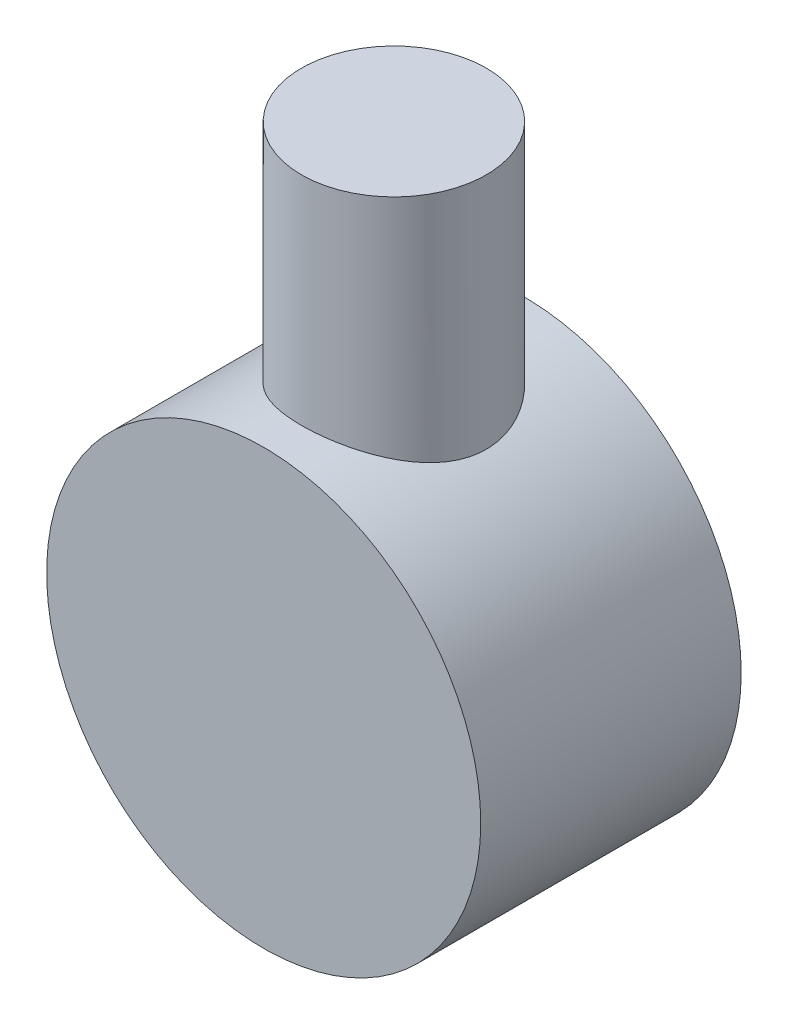
SolidWorks part; units mm, degrees
ref_plane "Front Plane" through (0, 0, 0) normal (0, 0, 1) x (1, 0, 0)
ref_plane "Top Plane" through (0, 0, 0) normal (0, 1, 0) x (1, 0, 0)
ref_plane "Right Plane" through (0, 0, 0) normal (1, 0, 0) x (0, 0, -1)
sketch "Sketch1" plane through (0, 0, 0) normal (0, 0, 1) x (1, 0, 0)
  circle A0 centre (0, 0) radius 25
  dimension "D1" = 50
extrude "Boss-Extrude1" add sketch "Sketch1" along normal mid plane 30
sketch "Sketch2" plane through (0, 0, 0) normal (0, 1, 0) x (1, 0, 0)
  circle A0 centre (0, 0) radius 10.65
  dimension "D1" = 21.3
extrude "Boss-Extrude2" add sketch "Sketch2" along normal blind 50
